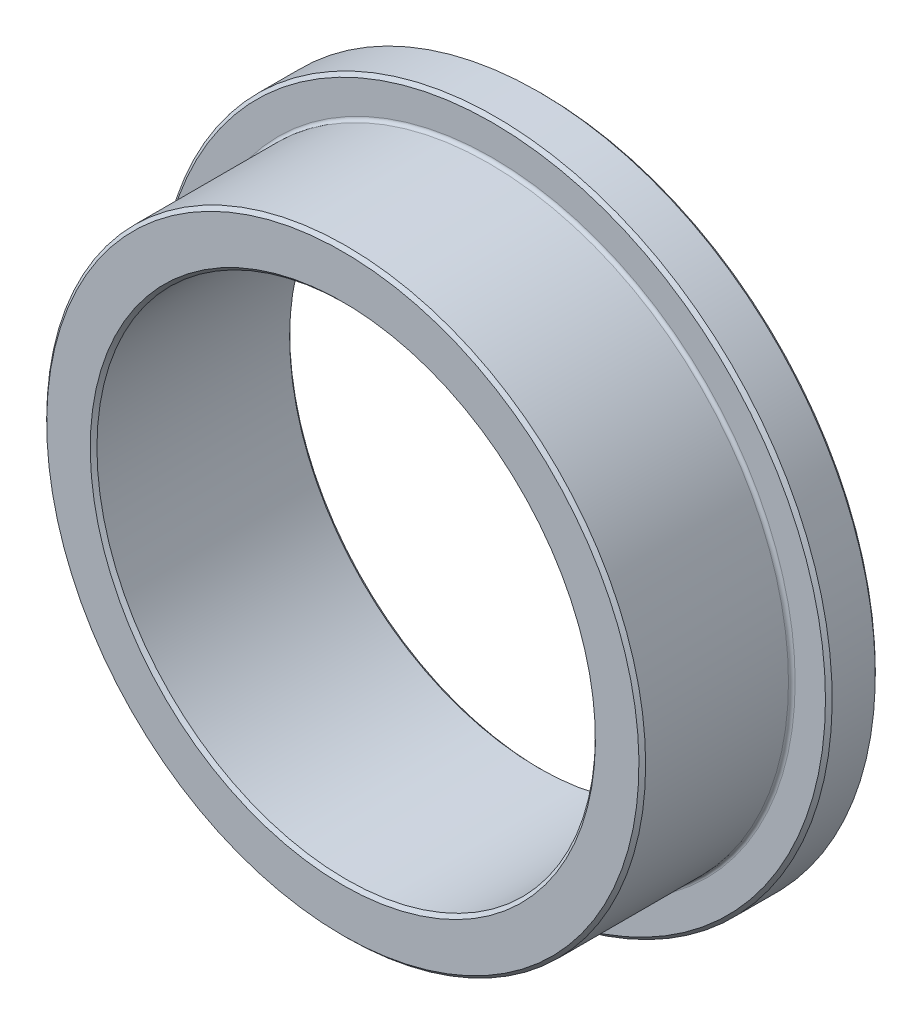
SolidWorks part; units mm, degrees
ref_plane "Front Plane" through (0, 0, 0) normal (0, 0, 1) x (1, 0, 0)
ref_plane "Top Plane" through (0, 0, 0) normal (0, 1, 0) x (1, 0, 0)
ref_plane "Right Plane" through (0, 0, 0) normal (1, 0, 0) x (0, 0, -1)
sketch "Sketch1" plane through (0, 0, 0) normal (0, 0, 1) x (1, 0, 0)
  circle A0 centre (0, 0) radius 19.0754 construction
  circle A1 centre (0, 0) radius 21.4312 construction
  circle A2 centre (0, 0) radius 15.875 construction
  point P5 (0, -21.4312)
  point P6 (0, -19.0754)
  point P7 (0, -15.875)
  point P8 (0, 15.875)
  point P9 (0, 19.0754)
  point P10 (0, 21.4312)
  dimension "Flange OD" = 42.8625
  dimension "ID" = 31.75
  dimension "OD" = 38.1508
sketch "Sketch2" plane through (0, 0, 0) normal (1, 0, 0) x (0, 0, -1)
  line L0 (-6.35, 21.4312) -> (6.35, 21.4312) construction
  line L1 (3.175, -21.4312) -> (6.35, -21.4313) construction
  line L2 (-6.35, 21.4312) -> (-6.35, 19.0754) construction
  line L4 (-6.35, 0) -> (6.35, 0) construction
  point P2 (0, 0)
  point P6 (0, 21.4312)
  dimension "Length" = 12.7
  dimension "Flange Thickness" = 3.175
sketch "Sketch4" plane through (0, 0, 0) normal (1, 0, 0) x (0, 0, -1)
  line L0 (3.175, -21.4312) -> (6.35, -21.4313)
  line L1 (6.35, -21.4313) -> (6.35, -15.875)
  line L2 (6.35, -15.875) -> (-6.35, -15.875)
  line L3 (-6.35, -15.875) -> (-6.35, -19.0754)
  line L4 (-6.35, -19.0754) -> (3.175, -19.0754)
  line L5 (3.175, -19.0754) -> (3.175, -21.4312)
revolve "Revolve1" add sketch "Sketch4" angle 360 about L4
fillet "Fillet1" radius 0.2134 5 edges at (0, -15.875, -6.35) (0, -15.875, 6.35) (0, -21.4313, -6.35) (0, -21.4312, -3.175) (0, -19.0754, 6.35) profile chamfer
fillet "Fillet2" radius 0.2134 1 edges at (0, -19.0754, -3.175)
equation "\"D1@Fillet1\"=(\"OD@Sketch1\"-\"ID@Sketch1\")/30"
equation "\"D1@Fillet2\"=(\"OD@Sketch1\"-\"ID@Sketch1\")/30"
